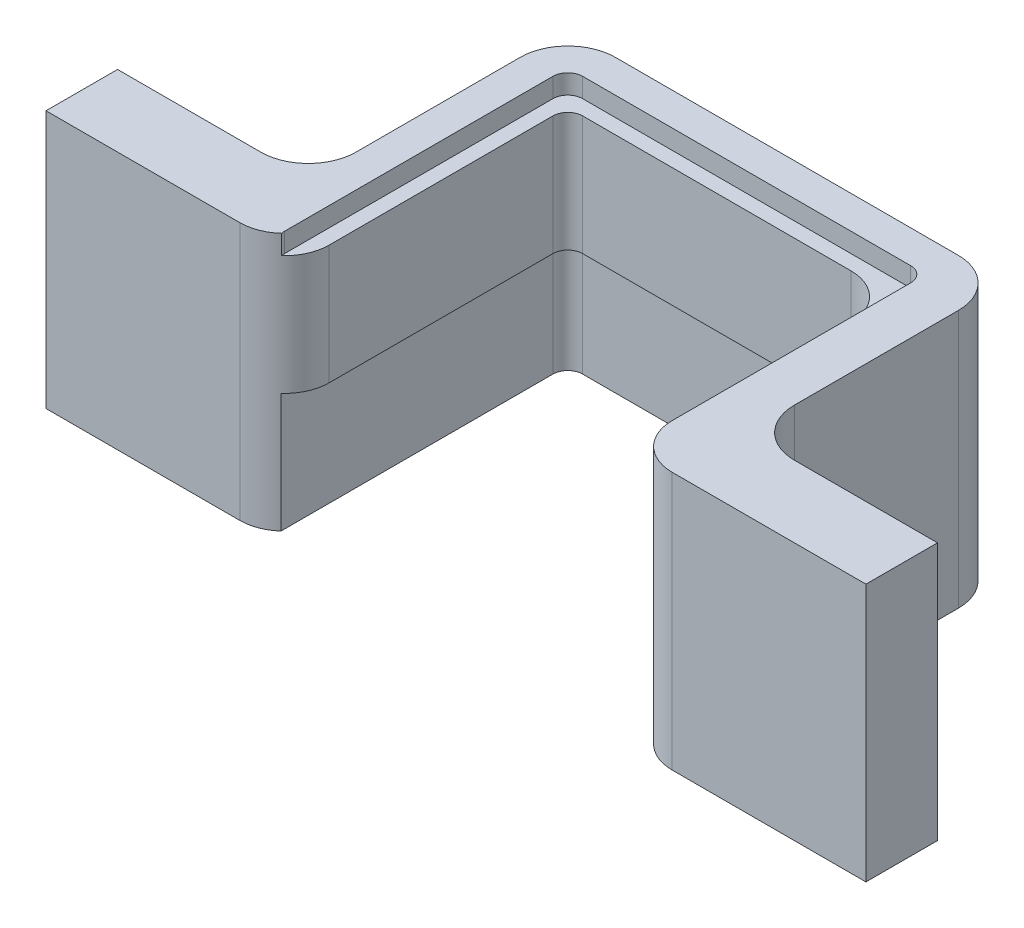
SolidWorks part; units mm, degrees
ref_plane "Front Plane" through (0, 0, 0) normal (0, 0, 1) x (1, 0, 0)
ref_plane "Top Plane" through (0, 0, 0) normal (0, 1, 0) x (1, 0, 0)
ref_plane "Right Plane" through (0, 0, 0) normal (1, 0, 0) x (0, 0, -1)
sketch "Sketch1" plane through (0, 0, 0) normal (0, 1, 0) x (1, 0, 0)
  line L0 (-5.5, -3.002) -> (-5.5, 4)
  line L1 (-5.5, -5) -> (5.5, -5) construction
  line L2 (-6, -4.5) -> (-6, 4.5) construction
  line L3 (-5.5, 5) -> (5.5, 5) construction
  line L4 (6, -4.5) -> (6, 4.5) construction
  line L5 (-6, -5) -> (6, 5) construction
  line L6 (-6, 5) -> (6, -5) construction
  line L7 (4, 4.5) -> (-5, 4.5)
  line L8 (-5.5, -3.002) -> (-5.5, -3.5)
  line L9 (-7, -5) -> (-13.5, -5)
  line L10 (5.5, 1.5) -> (6, 1.5)
  line L11 (5.5, 3) -> (5.5, 1.5)
  line L12 (6, 1.5) -> (6, -3.5)
  line L13 (7.5, -5) -> (14, -5)
  line L14 (-13.5, -5) -> (-13.5, -2.6)
  line L15 (-13.5, -2.6) -> (-8.7, -2.6)
  line L16 (-7.1, -1) -> (-7.1, 4.5)
  line L17 (-5.5, 6.1) -> (6, 6.1)
  line L18 (7.6, 4.5) -> (7.6, -1)
  line L19 (9.2, -2.6) -> (14, -2.6)
  line L20 (14, -2.6) -> (14, -5)
  arc A0 (5.5, 5) -> (6, 4.5) centre (5.5, 4.5) cw construction
  arc A1 (6, -4.5) -> (5.5, -5) centre (5.5, -4.5) cw construction
  arc A2 (-5.5, -5) -> (-6, -4.5) centre (-5.5, -4.5) cw construction
  arc A3 (-6, 4.5) -> (-5.5, 5) centre (-5.5, 4.5) cw construction
  circle A4 centre (-4, -3.002) radius 1.5 construction
  circle A5 centre (4, 3) radius 1.5 construction
  arc A6 (4, 4.5) -> (5.5, 3) centre (4, 3) cw
  arc A7 (-5.5, 4) -> (-5, 4.5) centre (-5, 4) cw
  arc A8 (-7, -5) -> (-5.5, -3.5) centre (-7, -3.5) ccw
  arc A9 (7.5, -5) -> (6, -3.5) centre (7.5, -3.5) cw
  arc A10 (-8.7, -2.6) -> (-7.1, -1) centre (-8.7, -1) ccw
  arc A11 (9.2, -2.6) -> (7.6, -1) centre (9.2, -1) cw
  arc A12 (6, 6.1) -> (7.6, 4.5) centre (6, 4.5) cw
  arc A13 (-7.1, 4.5) -> (-5.5, 6.1) centre (-5.5, 4.5) cw
  point P0 (0, 0)
  dimension "D3" = 0.5
  dimension "D4" = 3
  dimension "D5" = 3
  dimension "D10" = 0.5
  dimension "D16" = 1.5
  dimension "D17" = 1.5
  dimension "D18" = 1.6
  dimension "D19" = 1.6
  dimension "D20" = 1.6
  dimension "D21" = 1.6
  dimension "D1" = 12
  dimension "D2" = 10
  dimension "D6" = 2
  dimension "D7" = 1.998
  dimension "D8" = 2
  dimension "D9" = 2
  dimension "D11" = 2.4
  dimension "D12" = 1.6
  dimension "D13" = 1.6
  dimension "D14" = 1.6
  dimension "D15" = 2.4
  dimension "D22" = 8
  dimension "D23" = 8
extrude "Boss-Extrude1" add sketch "Sketch1" along normal blind 4
sketch "Sketch2" plane through (0, 4, 0) normal (0, 1, 0) x (1, 0, 0)
  line L0 (-13.5, -5) -> (-7, -5)
  line L1 (-13.5, -2.6) -> (-13.5, -5)
  line L2 (-6, -4.5) -> (-6, 4.5)
  line L3 (-5.5, 5) -> (5.5, 5)
  line L4 (6, -3.5) -> (6, 4.5)
  line L5 (-6, -5) -> (6, 5) construction
  line L6 (-6, 5) -> (6, -5) construction
  line L7 (-5.5, 6.1) -> (6, 6.1)
  line L8 (-7.1, 4.5) -> (-7.1, -1)
  line L9 (14, -5) -> (7.5, -5)
  line L10 (7.6, 4.5) -> (7.6, -1)
  line L11 (-13.5, -2.6) -> (-8.7, -2.6)
  line L12 (7.5, -5) -> (14, -5) construction
  line L15 (14, -2.6) -> (9.2, -2.6)
  line L16 (14, -2.6) -> (14, -5)
  arc A0 (6, 4.5) -> (5.5, 5) centre (5.5, 4.5) ccw
  arc A2 (-8.7, -2.6) -> (-7.1, -1) centre (-8.7, -1) ccw
  arc A3 (-6, 4.5) -> (-5.5, 5) centre (-5.5, 4.5) cw
  arc A4 (-5.9883, -4.6075) -> (-7, -5) centre (-7, -3.5) cw
  arc A5 (-5.9883, -4.6075) -> (-6, -4.5) centre (-5.5, -4.5) cw
  arc A6 (-7.1, 4.5) -> (-5.5, 6.1) centre (-5.5, 4.5) cw
  arc A7 (7.6, 4.5) -> (6, 6.1) centre (6, 4.5) ccw
  arc A8 (7.6, -1) -> (9.2, -2.6) centre (9.2, -1) ccw
  arc A9 (6, -3.5) -> (7.5, -5) centre (7.5, -3.5) ccw
  point P0 (0, 0)
  dimension "D3" = 0.5
  dimension "D7" = 1.6
  dimension "D8" = 1.6
  dimension "D9" = 1.6
  dimension "D10" = 1.6
  dimension "D1" = 12
  dimension "D2" = 10
  dimension "D4" = 7.1
  dimension "D5" = 7.6
  dimension "D6" = 6.1
extrude "Boss-Extrude2" add sketch "Sketch2" along normal blind 0.65
sketch "Sketch3" plane through (0, 0, 0) normal (0, -1, 0) x (1, 0, 0)
  line L0 (7.6, 1) -> (7.6, -4.5)
  line L1 (-5.5, -5) -> (5.5, -5)
  line L2 (-6, -4.5) -> (-6, 4.5)
  line L4 (6, -4.5) -> (6, 3.5)
  line L5 (-6, -5) -> (6, 5) construction
  line L6 (-6, 5) -> (6, -5) construction
  line L7 (14, 2.6) -> (9.2, 2.6)
  line L8 (14, 2.6) -> (14, 5)
  line L9 (14, 5) -> (7.5, 5)
  line L10 (6, 2.6) -> (6, 3.5)
  line L11 (-13.5, 2.6) -> (-8.7, 2.6)
  line L12 (-13.5, 2.6) -> (-13.5, 5)
  line L13 (-13.5, 5) -> (-7, 5)
  line L14 (-6, 2.6) -> (-6, 4.618)
  line L15 (-7.1, 1) -> (-7.1, -4.5)
  line L16 (-5.5, -6.1) -> (6, -6.1)
  arc A0 (-5.5, -6.1) -> (-7.1, -4.5) centre (-5.5, -4.5) cw
  arc A1 (7.6, -4.5) -> (6, -6.1) centre (6, -4.5) cw
  arc A2 (-7.1, 1) -> (-8.7, 2.6) centre (-8.7, 1) ccw
  arc A3 (7.6, 1) -> (9.2, 2.6) centre (9.2, 1) cw
  arc A4 (-5.5, -5) -> (-6, -4.5) centre (-5.5, -4.5) cw
  arc A5 (6, -4.5) -> (5.5, -5) centre (5.5, -4.5) cw
  arc A7 (-5.5, 5) -> (-5.84, 4.8666) centre (-5.5, 4.5) ccw
  arc A8 (-6, 4.618) -> (-7, 5) centre (-7, 3.5) ccw
  arc A9 (6, 3.5) -> (7.5, 5) centre (7.5, 3.5) cw
  arc A10 (7.5, 5) -> (6, 3.5) centre (7.5, 3.5) ccw construction
  point P0 (0, 0)
  arc M4 (-5.5, 3.5) -> (-7, 5) centre (-7, 3.5) ccw
  line M5 (-7, 5) -> (-13.5, 5)
  line M6 (-13.5, 5) -> (-13.5, 2.6)
  line M7 (-13.5, 2.6) -> (-8.7, 2.6)
  arc M8 (-8.7, 2.6) -> (-7.1, 1) centre (-8.7, 1) cw
  line M9 (-7.1, 1) -> (-7.1, -4.5)
  arc M10 (-7.1, -4.5) -> (-5.5, -6.1) centre (-5.5, -4.5) ccw
  line M11 (-5.5, -6.1) -> (6, -6.1)
  arc M12 (6, -6.1) -> (7.6, -4.5) centre (6, -4.5) ccw
  line M13 (7.6, -4.5) -> (7.6, 1)
  arc M14 (7.6, 1) -> (9.2, 2.6) centre (9.2, 1) cw
  line M15 (9.2, 2.6) -> (14, 2.6)
  line M16 (14, 2.6) -> (14, 5)
  line M17 (14, 5) -> (7.5, 5)
  arc M18 (7.5, 5) -> (6, 3.5) centre (7.5, 3.5) ccw
  line M19 (6, 3.5) -> (6, -1.5)
  dimension "D3" = 1.6
  dimension "D4" = 1.6
  dimension "D5" = 1.6
  dimension "D6" = 1.6
  dimension "D7" = 0.5
  dimension "D8" = 0.5
  dimension "D10" = 0.5
  dimension "D1" = 12
  dimension "D2" = 10
extrude "Boss-Extrude3" add sketch "Sketch3" along normal blind 4 contours L4 A5 L1 A4 L2 L14 M4 M5 M6 M7 M8 M9 M10 M11 M12 M13 M14 M15 M16 M17 M18 M19
